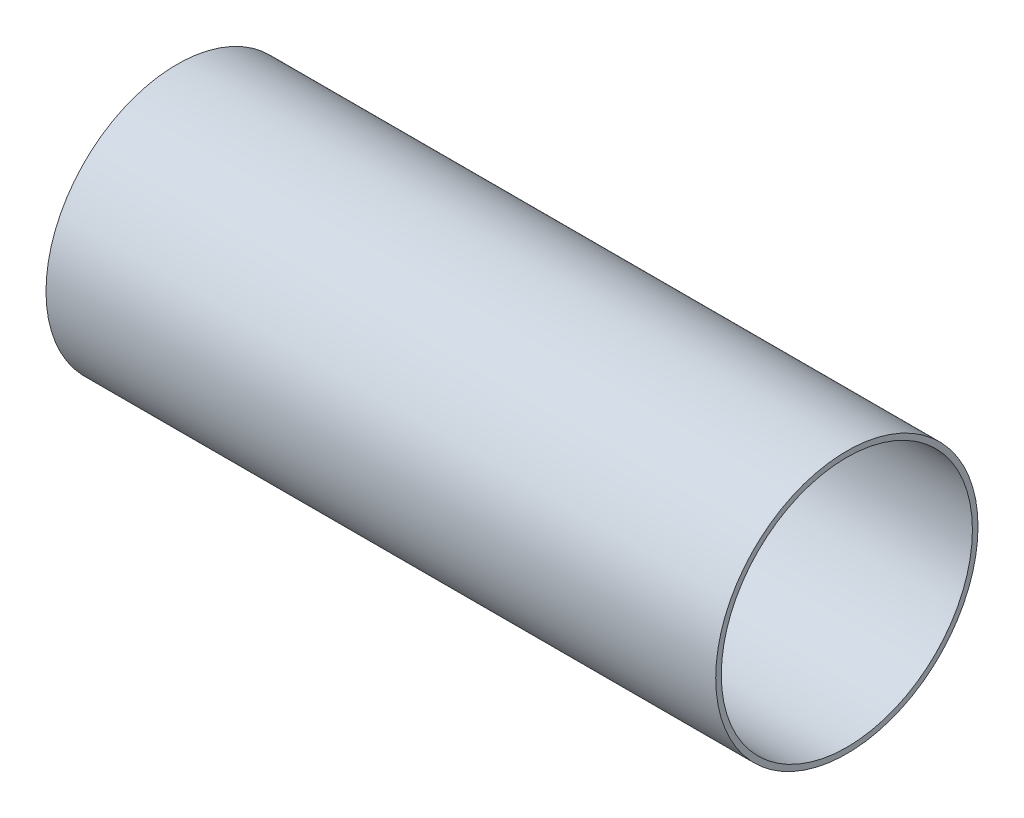
SolidWorks part; units mm, degrees
material "Air"
ref_plane "Front" through (0, 0, 0) normal (0, 0, 1) x (1, 0, 0)
ref_plane "Top" through (0, 0, 0) normal (0, 1, 0) x (1, 0, 0)
ref_plane "Right" through (0, 0, 0) normal (1, 0, 0) x (0, 0, -1)
sketch "Sketch2" plane through (0, 0, 0) normal (1, 0, 0) x (0, 0, -1)
  circle A0 centre (0, 0) radius 57.15
  dimension "D1" = 114.3
extrude "Extrude-Thin1" add sketch "Sketch2" along normal blind 304.8 thin
